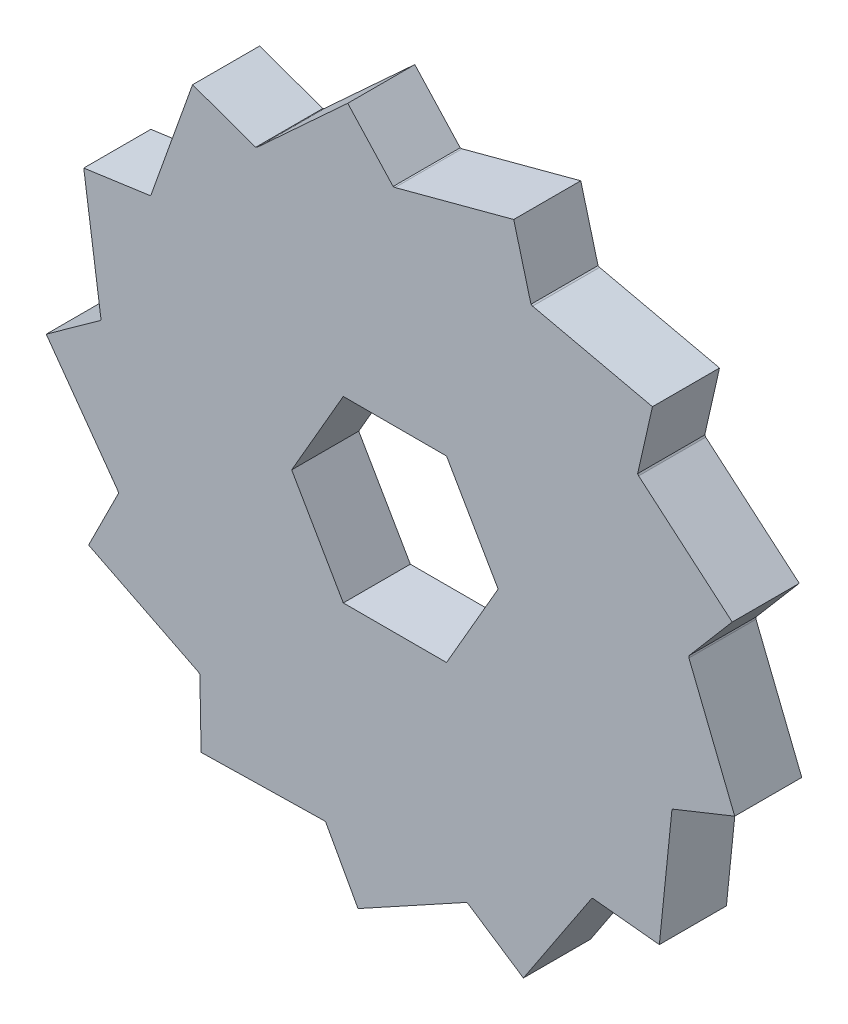
SolidWorks part; units mm, degrees
ref_plane "Front Plane" through (0, 0, 0) normal (0, 0, 1) x (1, 0, 0)
ref_plane "Top Plane" through (0, 0, 0) normal (0, 1, 0) x (1, 0, 0)
ref_plane "Right Plane" through (0, 0, 0) normal (1, 0, 0) x (0, 0, -1)
sketch "Sketch1" plane through (0, 0, 0) normal (0, 0, 1) x (1, 0, 0)
  line L6 (0, 0) -> (0, 21.0344) construction
  line L7 (0, 21.0344) -> (8.4363, 23.2847)
  line L8 (8.4363, 23.2847) -> (9.6637, 18.6831)
  line L9 (18.2909, 16.697) -> (17.2393, 12.0521)
  line L10 (9.7752, 18.625) -> (18.2909, 16.697)
  line L11 (23.9553, 6.2843) -> (20.8655, 2.6601)
  line L12 (17.311, 11.9489) -> (23.9553, 6.2843)
  line L13 (24.1318, -5.5681) -> (19.7117, -7.3413)
  line L14 (20.881, 2.5354) -> (24.1318, -5.5681)
  line L15 (18.78, -16.1449) -> (14.0422, -15.6608)
  line L16 (19.6675, -7.4589) -> (18.78, -16.1449)
  line L17 (9.126, -23.0231) -> (5.1558, -20.3927)
  line L18 (13.9484, -15.7445) -> (9.126, -23.0231)
  line L19 (-2.6187, -24.627) -> (-4.9118, -20.4529)
  line L20 (5.0339, -20.4232) -> (-2.6187, -24.627)
  line L21 (-13.7635, -20.5891) -> (-13.8541, -15.8275)
  line L22 (-5.0339, -20.4232) -> (-13.7635, -20.5891)
  line L23 (-21.7552, -11.8345) -> (-19.6226, -7.5763)
  line L24 (-13.9484, -15.7445) -> (-21.7552, -11.8345)
  line L25 (-24.7631, -0.3688) -> (-20.8958, 2.4106)
  line L26 (-19.6675, -7.4589) -> (-24.7631, -0.3688)
  line L27 (-22.098, 11.1814) -> (-17.382, 11.8453)
  line L28 (-20.881, 2.5354) -> (-22.098, 11.1814)
  line L29 (-14.3706, 20.1701) -> (-9.8863, 18.5663)
  line L30 (-17.311, 11.9489) -> (-14.3706, 20.1701)
  line L31 (-3.351, 24.5381) -> (-0.1257, 21.034)
  line L32 (-9.7752, 18.625) -> (-3.351, 24.5381)
  arc A0 (0, 21.0344) -> (-0.1257, 21.034) centre (0, 0) ccw
  arc A1 (-9.7752, 18.625) -> (-9.8863, 18.5663) centre (0, 0) ccw
  arc A2 (-17.311, 11.9489) -> (-17.382, 11.8453) centre (0, 0) ccw
  arc A3 (-20.881, 2.5354) -> (-20.8958, 2.4106) centre (0, 0) ccw
  arc A4 (-19.6675, -7.4589) -> (-19.6226, -7.5763) centre (0, 0) ccw
  arc A5 (-13.9484, -15.7445) -> (-13.8541, -15.8275) centre (0, 0) ccw
  arc A6 (-5.0339, -20.4232) -> (-4.9118, -20.4529) centre (0, 0) ccw
  arc A7 (5.0339, -20.4232) -> (5.1558, -20.3927) centre (0, 0) ccw
  arc A8 (13.9484, -15.7445) -> (14.0422, -15.6608) centre (0, 0) ccw
  arc A9 (19.6675, -7.4589) -> (19.7117, -7.3413) centre (0, 0) ccw
  arc A10 (20.881, 2.5354) -> (20.8655, 2.6601) centre (0, 0) ccw
  arc A11 (17.311, 11.9489) -> (17.2393, 12.0521) centre (0, 0) ccw
  arc A12 (9.7752, 18.625) -> (9.6637, 18.6831) centre (0, 0) ccw
  point P44 (0, 0)
  dimension "D1" = 21.0344
  dimension "D2" = 90
  dimension "D3" = 8.7312
  dimension "D4" = 4.7625
  dimension "D5" = 13
extrude "Boss-Extrude1" add sketch "Sketch1" along normal blind 4.7625
sketch "Sketch2" plane through (0, 0, 0) normal (0, 0, -1) x (-1, 0, 0)
  line L1 (-7.3323, 0) -> (-3.6662, -6.35)
  line L2 (-3.6662, -6.35) -> (3.6662, -6.35)
  line L3 (3.6662, -6.35) -> (7.3323, 0)
  line L4 (7.3323, 0) -> (3.6662, 6.35)
  line L5 (3.6662, 6.35) -> (-3.6662, 6.35)
  line L6 (-3.6662, 6.35) -> (-7.3323, 0)
  circle A0 centre (0, 0) radius 6.35 construction
  dimension "D1" = 12.7
extrude "Cut-Extrude1" cut sketch "Sketch2" against normal up to surface (4.7625 mm away) up to face at (0, 0, 4.7625)
